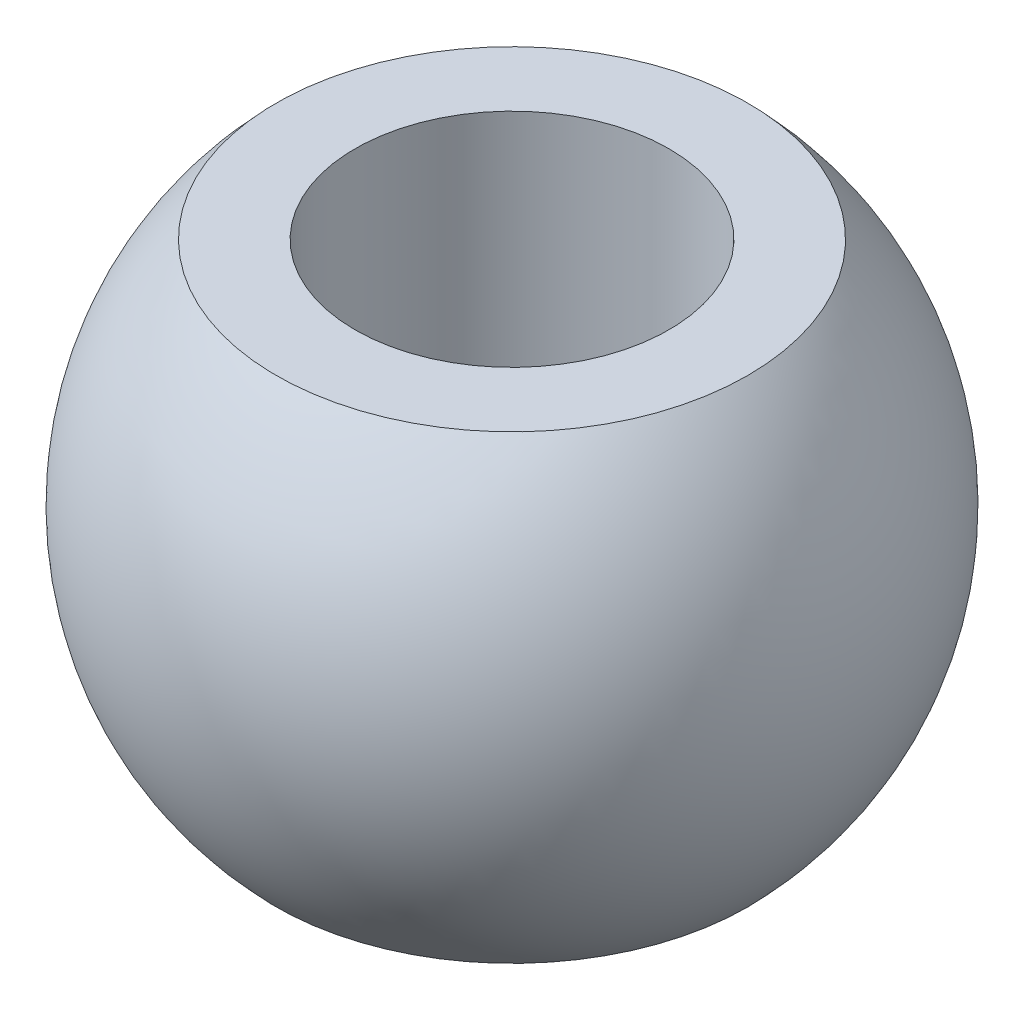
SolidWorks part; units mm, degrees
ref_plane "Front Plane" through (0, 0, 0) normal (0, 0, 1) x (1, 0, 0)
ref_plane "Top Plane" through (0, 0, 0) normal (0, 1, 0) x (1, 0, 0)
ref_plane "Right Plane" through (0, 0, 0) normal (1, 0, 0) x (0, 0, -1)
sketch "Sketch1" plane through (0, 0, 0) normal (0, 0, 1) x (1, 0, 0)
  line L0 (2.2544, 2.2) -> (1.5, 2.2)
  line L1 (1.5, 2.2) -> (1.5, -2.2)
  line L2 (1.5, -2.2) -> (2.2544, -2.2)
  line L3 (0, 2.0559) -> (0, -2.4729) construction
  arc A0 (2.2544, 2.2) -> (2.2544, -2.2) centre (0, 0) cw
  dimension "D1" = 3.15
  dimension "D2" = 4.4
  dimension "D3" = 1.5
revolve "Revolve1" add sketch "Sketch1" angle 360 about L3
